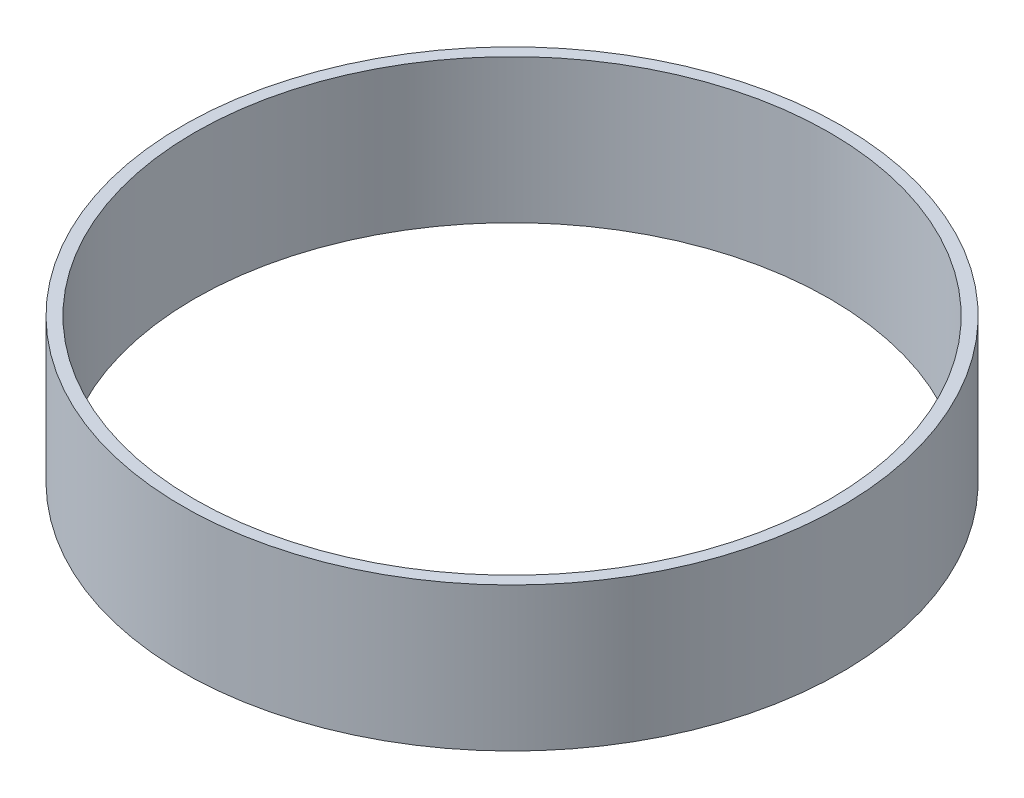
SolidWorks part; units mm, degrees
ref_plane "Front Plane" through (0, 0, 0) normal (0, 0, 1) x (1, 0, 0)
ref_plane "Top Plane" through (0, 0, 0) normal (0, 1, 0) x (1, 0, 0)
ref_plane "Right Plane" through (0, 0, 0) normal (1, 0, 0) x (0, 0, -1)
sketch "Sketch1" plane through (0, 0, 0) normal (0, 1, 0) x (1, 0, 0)
  circle A0 centre (0, 0) radius 84.1375
  circle A1 centre (0, 0) radius 87.3125
  dimension "D1" = 168.275
  dimension "D2" = 3.175
extrude "Boss-Extrude1" add sketch "Sketch1" along normal blind 38.1
